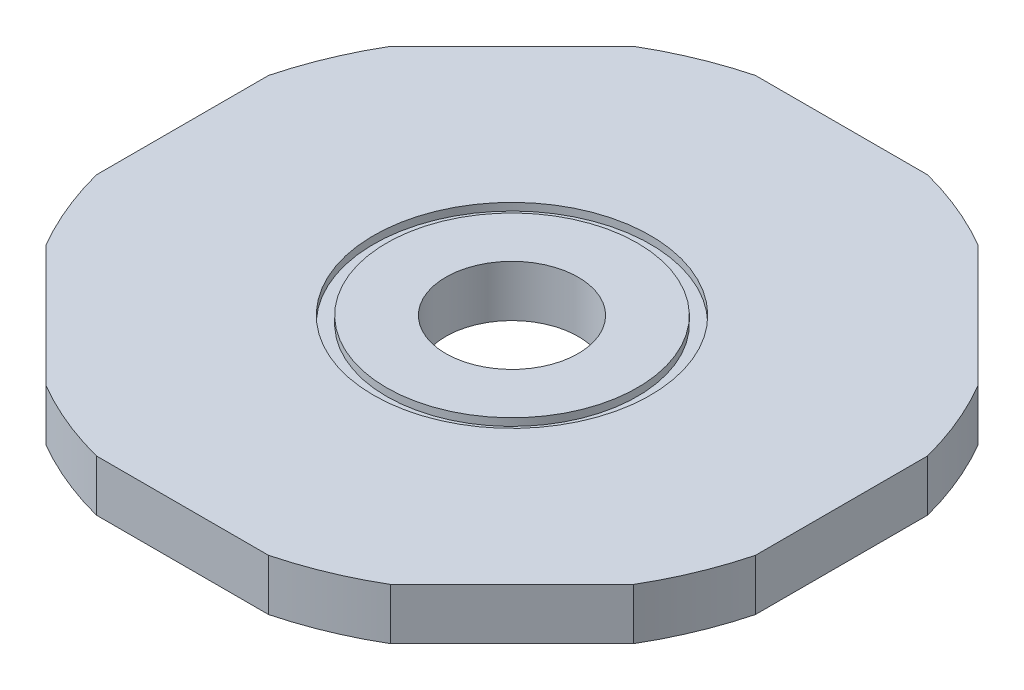
SolidWorks part; units mm, degrees
material "6061-T4 (SS)"
ref_plane "Front Plane" through (0, 0, 0) normal (0, 0, 1) x (1, 0, 0)
ref_plane "Top Plane" through (0, 0, 0) normal (0, 1, 0) x (1, 0, 0)
ref_plane "Right Plane" through (0, 0, 0) normal (1, 0, 0) x (0, 0, -1)
sketch "Sketch1" plane through (0, 0, 0) normal (0, 1, 0) x (1, 0, 0)
  line L1 (-50.6583, 122.3) -> (-122.3, 50.6583)
  line L2 (-122.3, 50.6583) -> (-122.3, -50.6583)
  line L3 (-122.3, -50.6583) -> (-50.6583, -122.3)
  line L4 (-50.6583, -122.3) -> (50.6583, -122.3)
  line L5 (50.6583, -122.3) -> (122.3, -50.6583)
  line L6 (122.3, -50.6583) -> (122.3, 50.6583)
  line L7 (122.3, 50.6583) -> (50.6583, 122.3)
  line L8 (50.6583, 122.3) -> (-50.6583, 122.3)
  circle A0 centre (0, 0) radius 122.3 construction
  circle A1 centre (0, 0) radius 126.4
  dimension "D2" = 252.8
  dimension "D1" = 244.6
extrude "Boss-Extrude1" add sketch "Sketch1" along normal blind 19.05 contours L4 A1 L5 L6 L7 L8 L1 L2 L3
sketch "Sketch3" plane through (0, 19.05, 0) normal (0, 1, 0) x (1, 0, 0)
  circle A0 centre (0, 0) radius 24.5745
  dimension "D1" = 49.149
extrude "Cut-Extrude1" cut sketch "Sketch3" against normal through all contours A0
sketch "Sketch5" plane through (0, 19.05, 0) normal (0, 1, 0) x (1, 0, 0)
  circle A0 centre (0, 0) radius 46.5455
  circle A1 centre (0, 0) radius 51.3715
  dimension "D1" = 93.091
  dimension "D2" = 102.743
extrude "Cut-Extrude2" cut sketch "Sketch5" against normal blind 2.794
sketch "Sketch7" plane through (0, 0, 0) normal (0, -1, 0) x (1, 0, 0)
  circle A0 centre (-71.374, 0) radius 4
  point P0 (-71.374, 0)
  dimension "D1" = 8
  dimension "D2" = 0
  dimension "D3" = 71.374
extrude "Cut-Extrude3" cut sketch "Sketch7" against normal blind 12.7 contours A0
thread "Thread1" pitch 1.25 start angle 0, offset 0, length 0, pitch 1.25, diameter 8
ref_plane "Plane1" through (-67.374, 0, 0) normal (0, 0, 1) x (1, 0, 0)
sketch "Thread Profile1" plane through (-67.374, 0, 0) normal (0, 0, 1) x (1, 0, 0)
  line L0 (0, 0) -> (0, 1.25) construction
  line L1 (0, 0) -> (0.6766, 0.3906)
  line L2 (0.6766, 0.3906) -> (0.6766, 0.5469)
  line L3 (0.6766, 0.5469) -> (0, 0.9375)
  line L4 (0.6766, 0.4687) -> (0, 0.4687) construction
  line L11 (0, 0) -> (0, 0.9375)
  point P2 (0, 0)
  dimension "Pitch" = 1.25
  dimension "Profile_Angle" = 60
  dimension "Profile_Land" = 0.1562
  dimension "Profile_Height" = 0.6766
hole_wizard "M8 Tapped Hole1" positions "Sketch16" profile "Sketch18" tap size "M8" standard "ISO"
sketch "Sketch16" plane through (0, 0, 0) normal (0, -1, 0) x (-1, 0, 0)
  point P4 (-71.374, 0)
  dimension "D1" = 71.374
sketch "Sketch18" plane through (71.374, 0, 0) normal (1, 0, 0) x (0, 0, -1)
  line L0 (0, 0) -> (0, 16)
  line L1 (0, 16) -> (3.4, 13.9571)
  line L2 (3.4, 13.9571) -> (3.4, 0.625)
  line L3 (3.4, 0.625) -> (4.025, 0)
  line L5 (4.025, 0) -> (0, 0)
  line L6 (-3.4, 0.625) -> (-4.025, 0) construction
  line L10 (0, 16) -> (-3.4, 13.9571) construction
  line L11 (0, -6.35) -> (0, 107.95) construction
  dimension "Tap Drill Dia." = 6.8
  dimension "Tap Drill Depth" = 16
  dimension "Near C'Sink Dia." = 8.05
  dimension "Near C'Sink Angle" = 90
  dimension "Drill Angle" = 118
cosmetic thread "Hole Thread1" parameters "D1"=16.002, "D2"=8
pattern_circular "CirPattern1" count 8 over 360 about axis through (0, 0, 0) along (0, 1, 0) of "Thread1", "Cut-Extrude3"
